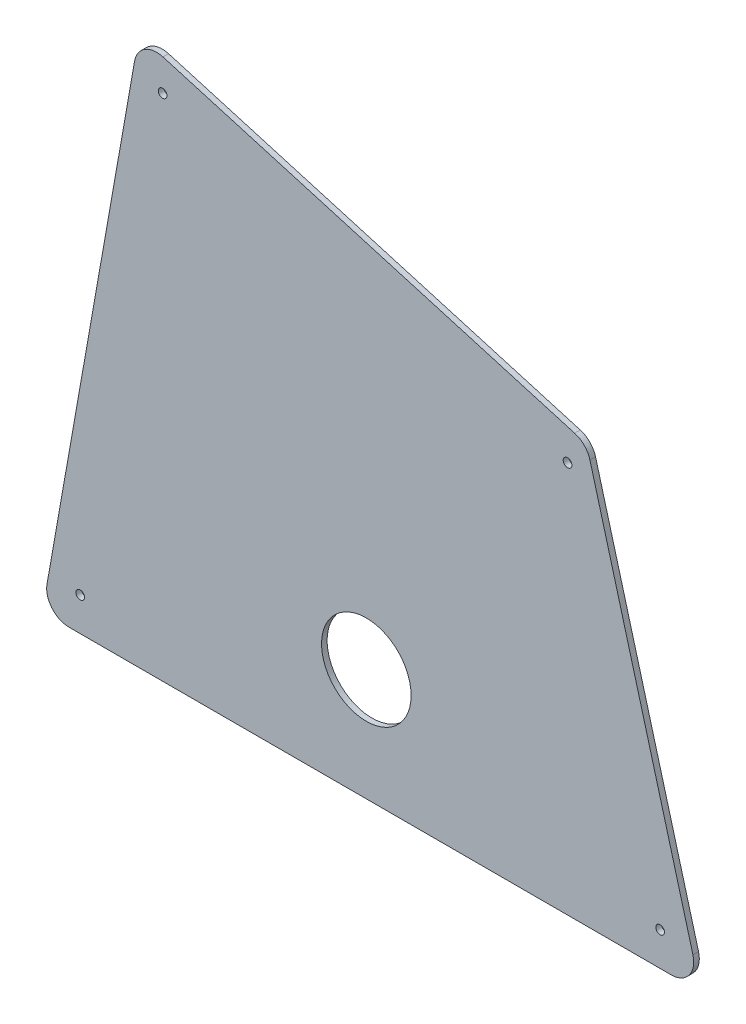
SolidWorks part; units mm, degrees
material "PC High Viscosity"
ref_plane "Front Plane" through (0, 0, 0) normal (0, 0, 1) x (1, 0, 0)
ref_plane "Top Plane" through (0, 0, 0) normal (0, 1, 0) x (1, 0, 0)
ref_plane "Right Plane" through (0, 0, 0) normal (1, 0, 0) x (0, 0, -1)
sketch "Sketch1" plane through (0, 0, 0) normal (0, 0, 1) x (1, 0, 0)
  line L0 (-115.3996, 121.8569) -> (118.1755, 53.7759)
  line L1 (-168.6745, -185.018) -> (173.0582, -185.018)
  line L2 (-181.1816, -170.1127) -> (-131.4605, 111.8696)
  line L4 (185.3093, -168.9711) -> (126.8727, 44.9302)
  line L5 (-183.8098, -185.018) -> (124.9995, 125.8211) construction
  line L6 (-129.0005, 125.8211) -> (189.6932, -185.018) construction
  arc A0 (-168.6745, -185.018) -> (-181.1816, -170.1127) centre (-168.6745, -172.318) cw
  arc A1 (173.0582, -185.018) -> (185.3093, -168.9711) centre (173.0582, -172.318) ccw
  arc A2 (118.1755, 53.7759) -> (126.8727, 44.9302) centre (114.6217, 41.5833) cw
  arc A3 (-131.4605, 111.8696) -> (-115.3996, 121.8569) centre (-118.9535, 109.6642) cw
  circle A4 centre (0, -121.518) radius 25.4
  point P0 (0, 0)
  point P19 (124.9995, 51.7869)
  dimension "D3" = 12.7
  dimension "D5" = 12.7
  dimension "D8" = 50.8
  dimension "D1" = 254
  dimension "D2" = 317.5
  dimension "D4" = 16.25
  dimension "D6" = 80
  dimension "D7" = 74.72
  dimension "D9" = 63.5
extrude "Boss-Extrude1" add sketch "Sketch1" along normal blind 3.175
sketch "Sketch3" plane through (0, 0, 3.175) normal (0, 0, 1) x (1, 0, 0)
  line L0 (-168.6745, -185.018) -> (173.0582, -185.018) construction
  point P0 (-162.3245, -165.968)
  point P1 (166.7082, -165.968)
  point P2 (114.1727, 37.232)
  point P3 (-115.5855, 103.907)
  dimension "D1" = 19.05
  dimension "D2" = 288.925
  dimension "D3" = 222.25
  dimension "D4" = 6.35
  dimension "D5" = 6.35
  dimension "D6" = 15.875
  dimension "D7" = 12.7
hole_wizard "#10 (0.1935) Diameter Hole1" positions "Sketch6" profile "Sketch7" hole size "#10" standard "ANSI Inch" end condition through all
sketch "Sketch6" plane through (0, 0, 3.175) normal (0, 0, 1) x (1, 0, 0)
  point P0 (-115.5855, 103.907)
  point P3 (114.1727, 37.232)
  point P6 (166.7082, -165.968)
  point P9 (-162.3245, -165.968)
sketch "Sketch7" plane through (-115.5855, 103.907, 3.175) normal (1, 0, 0) x (0, -1, 0)
  line L0 (0, 0) -> (0, 3.175)
  line L1 (0, 3.175) -> (2.4574, 3.175)
  line L2 (2.4574, 3.175) -> (2.4574, 0)
  line L5 (2.4574, 0) -> (0, 0)
  line L11 (0, -6.35) -> (0, 107.95) construction
  dimension "Thru Hole Dia." = 4.9149
  dimension "Thru Hole Depth" = 3.175
